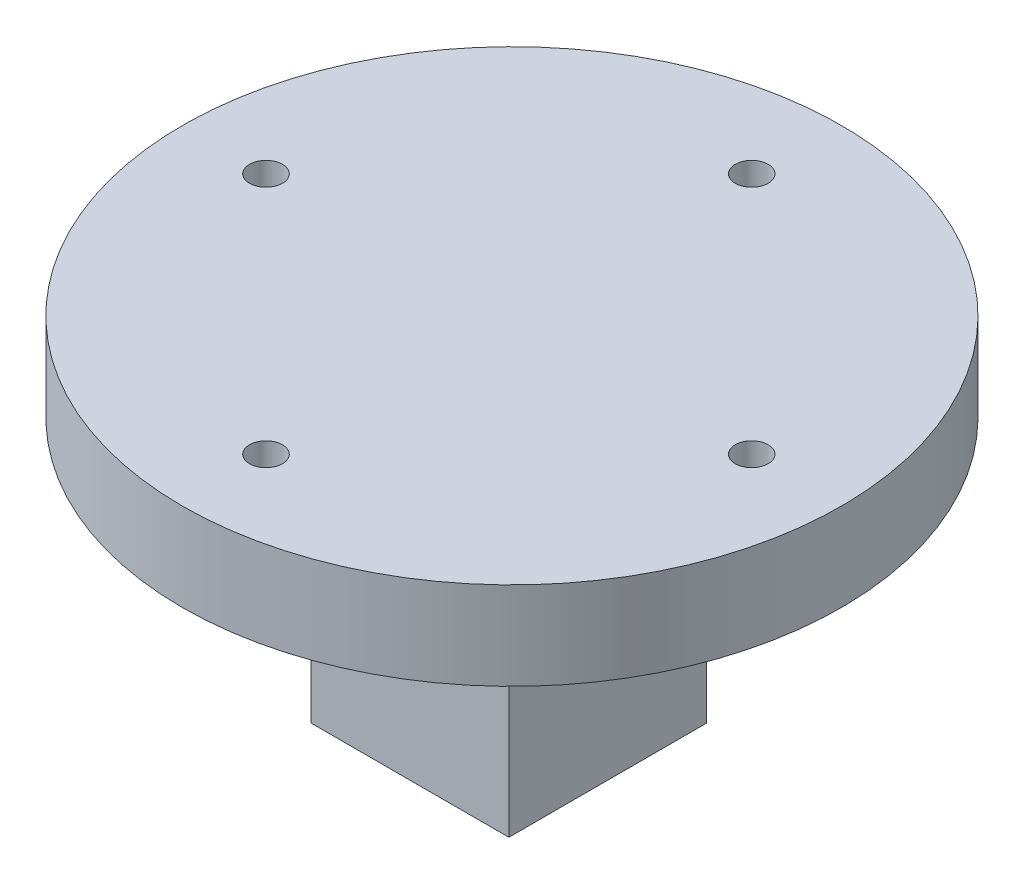
SolidWorks part; units mm, degrees
ref_plane "Front Plane" through (0, 0, 0) normal (0, 0, 1) x (1, 0, 0)
ref_plane "Top Plane" through (0, 0, 0) normal (0, 1, 0) x (1, 0, 0)
ref_plane "Right Plane" through (0, 0, 0) normal (1, 0, 0) x (0, 0, -1)
sketch "Sketch1" plane through (0, 0, 0) normal (0, 1, 0) x (1, 0, 0)
  line L1 (-3.2166, 16.4968) -> (4.2834, 16.4968) construction
  line L2 (-3.2166, 16.4968) -> (-3.2166, 11.6906) construction
  line L4 (4.2834, 16.4968) -> (4.2834, 11.3432) construction
  line L6 (-9, 9) -> (9, 9)
  line L15 (-9, 9) -> (-9, -9)
  line L16 (-9, -9) -> (9, -9)
  line L17 (9, 9) -> (9, -9)
  line L18 (-9, 9) -> (9, -9) construction
  line L19 (-9, -9) -> (9, 9) construction
  arc A0 (-3.2166, 11.6906) -> (-11.3432, 4.2834) centre (0, 0) ccw construction
  dimension "D1" = 24.25
  dimension "D2" = 7.5
  dimension "D3" = 18
  dimension "D4" = 18
extrude "Boss-Extrude1" add sketch "Sketch1" along normal blind 24.25
sketch "Sketch2" plane through (0, 24.25, 0) normal (0, 1, 0) x (1, 0, 0)
  circle A0 centre (0.28, 0) radius 30
  dimension "D1" = 60
extrude "Boss-Extrude2" add sketch "Sketch2" along normal blind 8
sketch "Sketch3" plane through (0, 32.25, 0) normal (0, 1, 0) x (1, 0, 0)
  circle A0 centre (0, 22.1067) radius 1.5
  circle A1 centre (22.1067, 0) radius 1.5
  circle A2 centre (0, -22.1067) radius 1.5
  circle A3 centre (-22.1067, 0) radius 1.5
  point P11 (0, 0)
  dimension "D1" = 4
extrude "Cut-Extrude1" cut sketch "Sketch3" against normal blind 12
